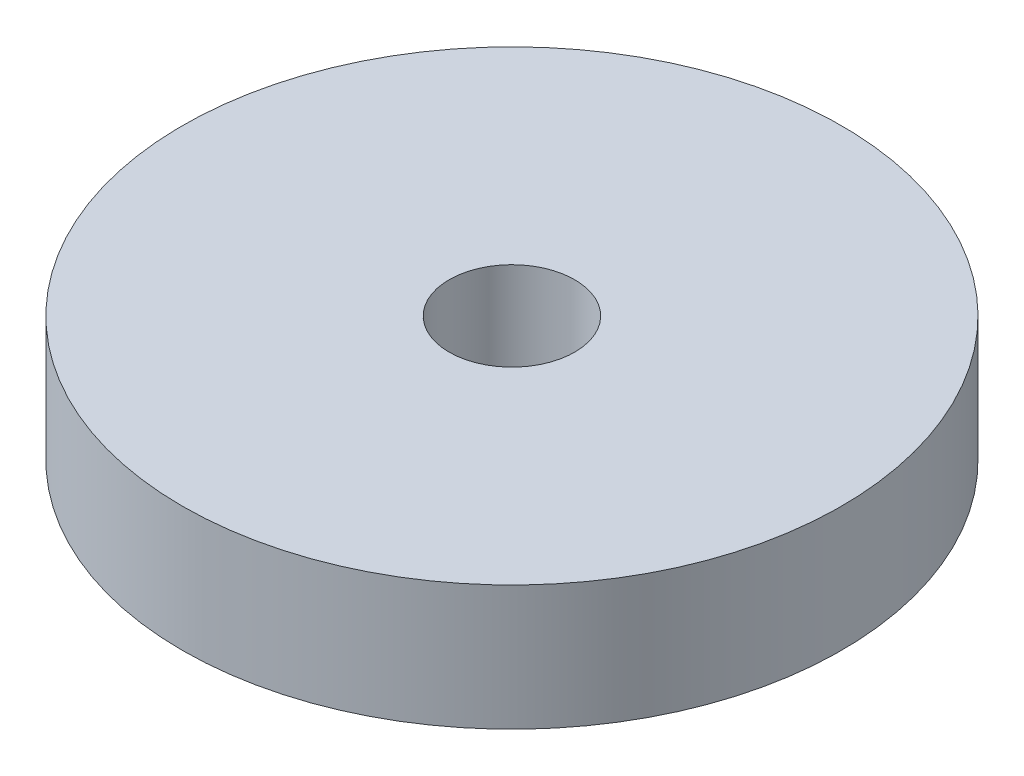
SolidWorks part; units mm, degrees
material "AISI 1020 Steel, Cold Rolled"
ref_plane "Front Plane" through (0, 0, 0) normal (0, 0, 1) x (1, 0, 0)
ref_plane "Top Plane" through (0, 0, 0) normal (0, 1, 0) x (1, 0, 0)
ref_plane "Right Plane" through (0, 0, 0) normal (1, 0, 0) x (0, 0, -1)
sketch "Sketch1" plane through (0, 0, 0) normal (0, 1, 0) x (1, 0, 0)
  circle A0 centre (0, 0) radius 14.986
  dimension "D1" = 29.972
extrude "Base" add sketch "Sketch1" along normal blind 10.16
sketch "Sketch2" plane through (0, 10.16, 0) normal (0, 1, 0) x (1, 0, 0)
  circle A0 centre (0, 0) radius 31.496
  dimension "D1" = 62.992
extrude "Gear" add sketch "Sketch2" along normal blind 11.938
sketch "Sketch3" plane through (0, 22.098, 0) normal (0, 1, 0) x (1, 0, 0)
  circle A0 centre (0, 0) radius 6
  dimension "D1" = 12
extrude "Cut-Extrude1" cut sketch "Sketch3" against normal through all
ref_plane "SpurGear-MidPlane" through (0, 16.129, 0) normal (0, 1, 0) x (1, 0, 0)
